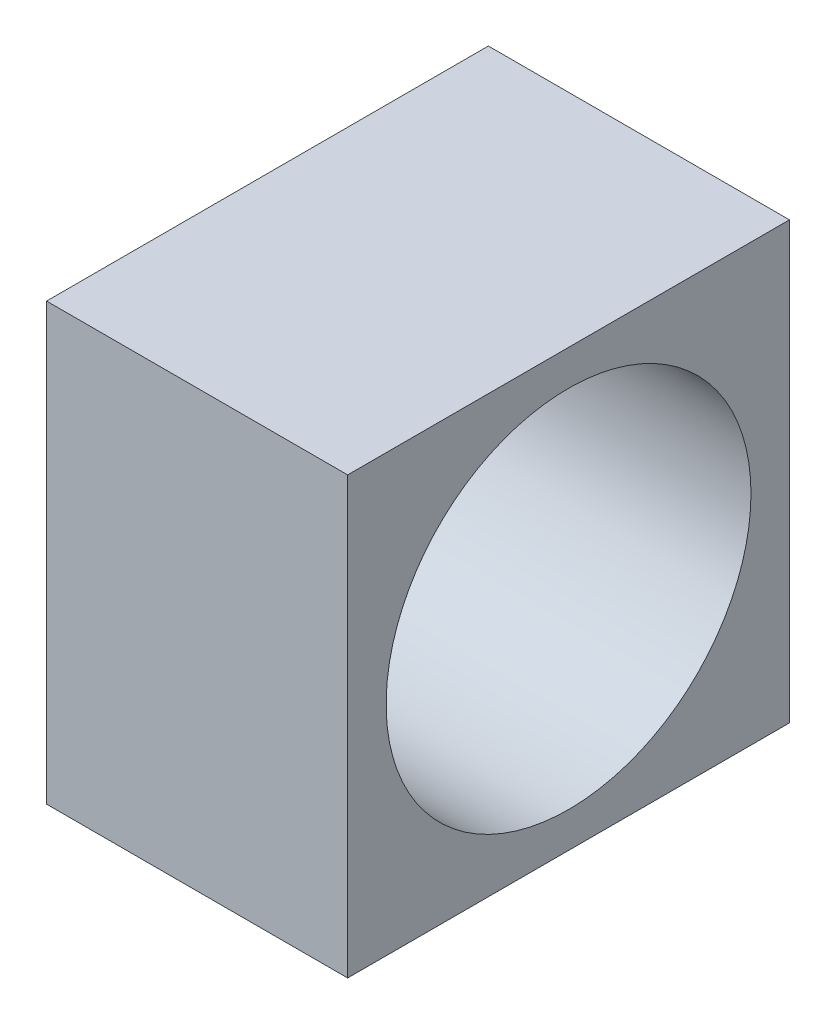
SolidWorks part; units mm, degrees
ref_plane "Front Plane" through (0, 0, 0) normal (0, 0, 1) x (1, 0, 0)
ref_plane "Top Plane" through (0, 0, 0) normal (0, 1, 0) x (1, 0, 0)
ref_plane "Right Plane" through (0, 0, 0) normal (1, 0, 0) x (0, 0, -1)
sketch "Sketch1" plane through (0, 0, 0) normal (1, 0, 0) x (0, 0, -1)
  line L1 (-6.2359, 6.15) -> (6.2359, 6.15)
  line L2 (-6.2359, 6.15) -> (-6.2359, -6.15)
  line L3 (-6.2359, -6.15) -> (6.2359, -6.15)
  line L4 (6.2359, 6.15) -> (6.2359, -6.15)
  line L5 (0, -6.15) -> (0, 6.15) construction
  line L6 (-6.2359, 0) -> (6.2359, 0) construction
  circle A0 centre (0, 0) radius 5.15
  point P3 (0, 0)
  point P8 (6.15, 0)
  dimension "D1" = 10.3
  dimension "D3" = 12.3
extrude "Boss-Extrude1" add sketch "Sketch1" along normal blind 8.5
